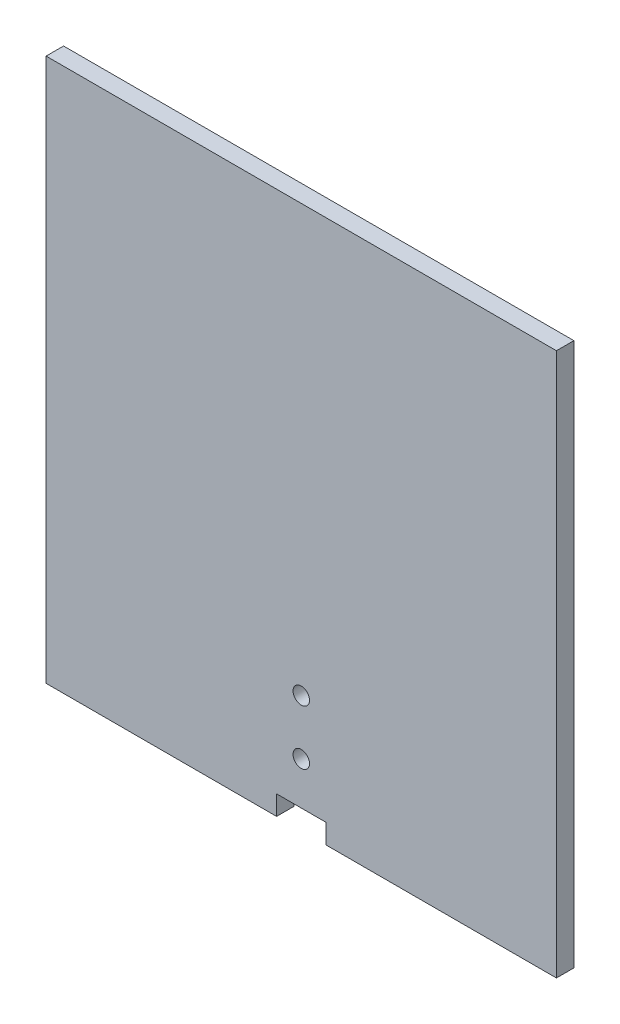
SolidWorks part; units mm, degrees
ref_plane "Front Plane" through (0, 0, 0) normal (0, 0, 1) x (1, 0, 0)
ref_plane "Top Plane" through (0, 0, 0) normal (0, 1, 0) x (1, 0, 0)
ref_plane "Right Plane" through (0, 0, 0) normal (1, 0, 0) x (0, 0, -1)
sketch "Sketch1" plane through (0, 0, 0) normal (0, 0, 1) x (1, 0, 0)
  line L0 (-46.5, 0) -> (46.5, 0) construction
  line L1 (-46.5, 49.5) -> (46.5, 49.5)
  line L2 (-46.5, 49.5) -> (-46.5, -49.5)
  line L3 (-46.5, -49.5) -> (46.5, -49.5)
  line L4 (46.5, 49.5) -> (46.5, -49.5)
  line L5 (-46.5, 49.5) -> (46.5, -49.5) construction
  line L6 (-46.5, -49.5) -> (46.5, 49.5) construction
  line L7 (0, 49.5) -> (0, -49.5) construction
  point P0 (0, 0)
  dimension "D1" = 93
  dimension "D2" = 99
extrude "Boss-Extrude1" add sketch "Sketch1" along normal blind 3.18
sketch "Sketch2" plane through (0, 0, 3.18) normal (0, 0, 1) x (1, 0, 0)
  circle A0 centre (0, -38.18) radius 1.5
  circle A1 centre (0, -28.18) radius 1.5
  dimension "D1" = 3
  dimension "D2" = 3
extrude "Cut-Extrude1" cut sketch "Sketch2" against normal blind 10
sketch "Sketch3" plane through (0, 0, 3.18) normal (0, 0, 1) x (1, 0, 0)
  line L0 (-46.5, -49.5) -> (46.5, -49.5) construction
  line L1 (4.5, -45.93) -> (-4.5, -45.93)
  line L2 (4.5, -45.93) -> (4.5, -49.5)
  line L3 (4.5, -49.5) -> (-4.5, -49.5)
  line L4 (-4.5, -45.93) -> (-4.5, -49.5)
  line L5 (-4.5, -45.93) -> (-4.5, -49.93) construction
extrude "Cut-Extrude2" cut sketch "Sketch3" against normal blind 10
